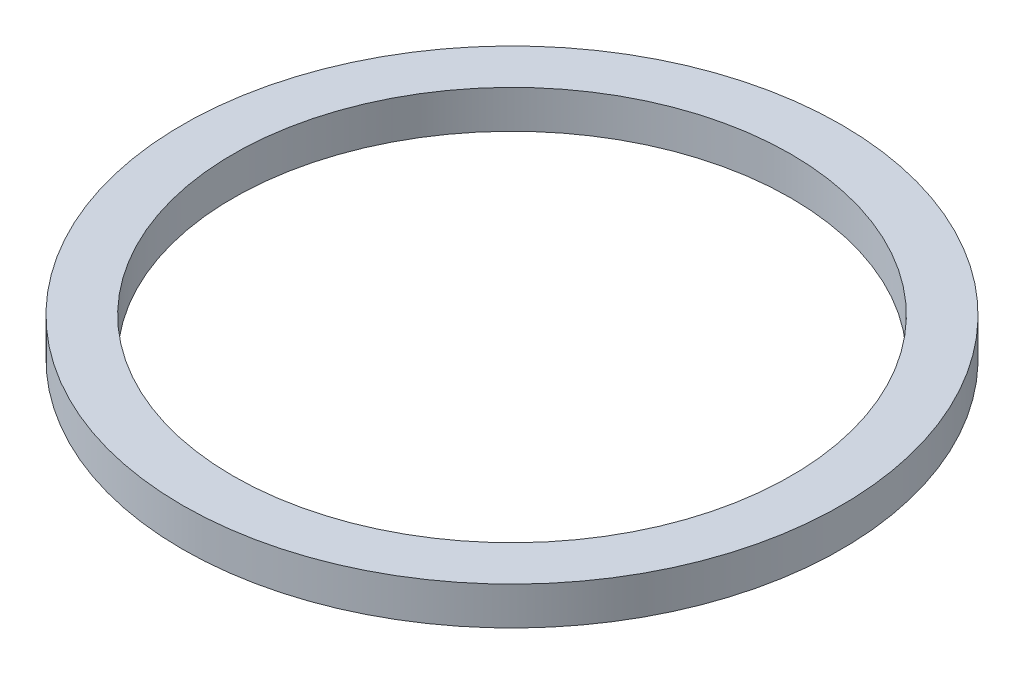
SolidWorks part; units mm, degrees
ref_plane "Front" through (0, 0, 0) normal (0, 0, 1) x (1, 0, 0)
ref_plane "Top" through (0, 0, 0) normal (0, 1, 0) x (1, 0, 0)
ref_plane "Right" through (0, 0, 0) normal (1, 0, 0) x (0, 0, -1)
sketch "Sketch1" plane through (0, 0, 0) normal (0, 1, 0) x (1, 0, 0)
  circle A0 centre (0, 0) radius 11
  circle A1 centre (0, 0) radius 13
  dimension "D1" = 22
  dimension "D2" = 26
extrude "Boss-Extrude1" add sketch "Sketch1" along normal blind 1.5
